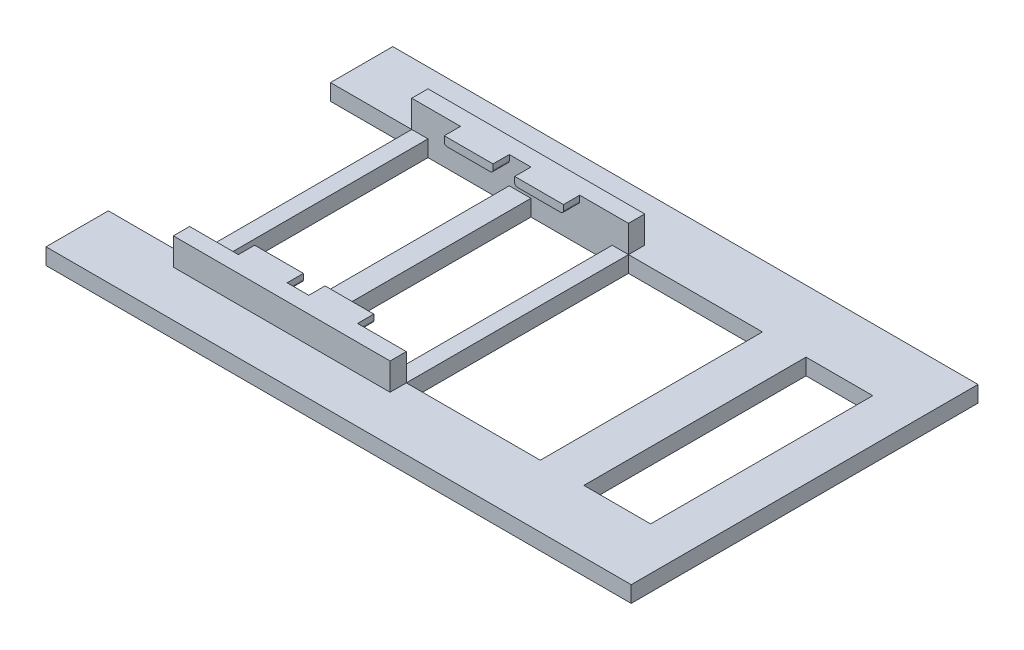
SolidWorks part; units mm, degrees
ref_plane "Alzado" through (0, 0, 0) normal (0, 0, 1) x (1, 0, 0)
ref_plane "Planta" through (0, 0, 0) normal (0, 1, 0) x (1, 0, 0)
ref_plane "Vista lateral" through (0, 0, 0) normal (1, 0, 0) x (0, 0, -1)
sketch "Croquis1" plane through (0, 0, 0) normal (0, 1, 0) x (1, 0, 0)
  line L0 (-2, 20.5) -> (-2, -20.5)
  line L1 (-20, -23.5) -> (20, -23.5)
  line L2 (-20, -23.5) -> (-20, 23.5)
  line L3 (-20, 23.5) -> (20, 23.5)
  line L4 (20, -23.5) -> (20, 23.5)
  line L5 (17, -20.5) -> (2, -20.5)
  line L6 (17, -20.5) -> (17, 20.5)
  line L7 (17, 20.5) -> (2, 20.5)
  line L8 (-17, -20.5) -> (-17, 20.5)
  line L9 (2, 20.5) -> (2, -20.5)
  line L10 (-2, -20.5) -> (-17, -20.5)
  line L11 (-2, 20.5) -> (-17, 20.5)
  line L12 (-55, 0) -> (55, 0) construction
  point P0 (0, 0)
  point P6 (0, 0)
  point P15 (-17, 0)
  dimension "D1" = 47
  dimension "D2" = 40
  dimension "D3" = 3
  dimension "D4" = 3
  dimension "D5" = 3
  dimension "D6" = 15
  dimension "D7" = 15
  dimension "D8" = 3
extrude "Saliente-Extruir1" add sketch "Croquis1" along normal blind 3
sketch "Croquis3" plane through (0, 3, 0) normal (0, 1, 0) x (1, 0, 0)
  line L0 (20, -23.5) -> (20, 23.5) construction
  line L1 (-20, 23.5) -> (20, 23.5)
  line L2 (-20, 23.5) -> (-20, 20.5)
  line L3 (-20, 20.5) -> (20, 20.5)
  line L4 (20, 23.5) -> (20, 20.5)
  line L6 (-20, -23.5) -> (20, -23.5)
  line L7 (-20, -23.5) -> (-20, -20.5)
  line L8 (-20, -20.5) -> (20, -20.5)
  line L9 (20, -23.5) -> (20, -20.5)
  dimension "D1" = 3
  dimension "D2" = 3
extrude "Saliente-Extruir2" add sketch "Croquis3" along normal blind 5
sketch "Croquis5" plane through (0, 0, -20.5) normal (0, 0, 1) x (1, 0, 0)
  line L0 (0, -55) -> (0, 55) construction
  line L1 (-10.5, 6.5) -> (-2.5, 6.5)
  line L2 (-11, 7) -> (-11, 8)
  line L3 (-11, 8) -> (-2, 8)
  line L4 (-2, 7) -> (-2, 8)
  line L5 (-11, 6.5) -> (-2, 8) construction
  line L6 (-11, 8) -> (-2, 6.5) construction
  line L7 (11, 8) -> (2, 6.5) construction
  line L8 (11, 6.5) -> (2, 8) construction
  line L9 (2, 7) -> (2, 8)
  line L10 (11, 8) -> (2, 8)
  line L11 (11, 7) -> (11, 8)
  line L12 (10.5, 6.5) -> (2.5, 6.5)
  line L13 (-20, 8) -> (20, 8) construction
  arc A0 (-2.5, 6.5) -> (-2, 7) centre (-2.5, 7) ccw
  arc A1 (-10.5, 6.5) -> (-11, 7) centre (-10.5, 7) cw
  arc A2 (10.5, 6.5) -> (11, 7) centre (10.5, 7) ccw
  arc A3 (2.5, 6.5) -> (2, 7) centre (2.5, 7) cw
  point P0 (-6.5, 7.25)
  point P11 (6.5, 7.25)
  dimension "D5" = 0.5
  dimension "D6" = 0.5
  dimension "D1" = 9
  dimension "D2" = 1.5
  dimension "D3" = 6.5
  dimension "D4" = 0
extrude "Saliente-Extruir3" add sketch "Croquis5" along normal blind 3
mirror "Simetría3" about plane through (0, 0, 0) normal (0, 0, 1) of "Saliente-Extruir3"
sketch "Croquis6" plane through (0, 0, 23.5) normal (0, 0, 1) x (1, 0, 0)
  line L0 (22, 0) -> (-22, 0) construction
  line L1 (-20, 0) -> (20, 0)
  line L2 (-20, 0) -> (-20, 3)
  line L3 (-20, 3) -> (20, 3)
  line L4 (20, 0) -> (20, 3)
  line L5 (-20, 8) -> (-20, 0) construction
  line L6 (20, 8) -> (20, 0) construction
  dimension "D1" = 3
extrude "Saliente-Extruir4" add sketch "Croquis6" along normal blind 8.5
mirror "Simetría4" about plane through (0, 0, 0) normal (0, 0, 1) of "Saliente-Extruir4"
sketch "Croquis7" plane through (-20, 0, 0) normal (-1, 0, 0) x (0, 0, 1)
  line L0 (22, 0) -> (-22, 0) construction
  line L1 (-32, 0) -> (-20.5, 0)
  line L2 (-32, 0) -> (-32, 3)
  line L3 (-32, 3) -> (-20.5, 3)
  line L4 (32, 0) -> (32, 3)
  line L5 (-32, 3) -> (-32, 0) construction
  line L6 (20.5, 3) -> (20.5, 0)
  line L7 (-20.5, 3) -> (-20.5, 0)
  line L8 (20.5, 3) -> (32, 3)
  line L9 (20.5, 0) -> (32, 0)
extrude "Saliente-Extruir5" add sketch "Croquis7" along normal blind 15
sketch "Croquis8" plane through (20, 0, 0) normal (1, 0, 0) x (0, 0, -1)
  line L0 (35.2021, 0) -> (-35.2021, 0) construction
  line L1 (-32, 3) -> (32.0038, 3)
  line L2 (-32, 3) -> (-32, 0)
  line L3 (-32, 0) -> (32.0038, 0)
  line L4 (32.0038, 3) -> (32.0038, 0)
  dimension "D1" = 64.0038
extrude "Saliente-Extruir7" add sketch "Croquis8" along normal blind 53
sketch "Croquis9" plane through (0, 3, 0) normal (0, 1, 0) x (1, 0, 0)
  line L1 (20, 20.5) -> (44.7231, 20.5)
  line L2 (20, 20.5) -> (20, -20.5)
  line L3 (20, -20.5) -> (44.7231, -20.5)
  line L4 (44.7231, 20.5) -> (44.7231, -20.5)
  line L5 (52.7692, 20.5) -> (65.0822, 20.5)
  line L6 (52.7692, 20.5) -> (52.7692, -20.5)
  line L7 (52.7692, -20.5) -> (65.0822, -20.5)
  line L8 (65.0822, 20.5) -> (65.0822, -20.5)
  dimension "D1" = 41
extrude "Cortar-Extruir1" cut sketch "Croquis9" against normal blind 53
